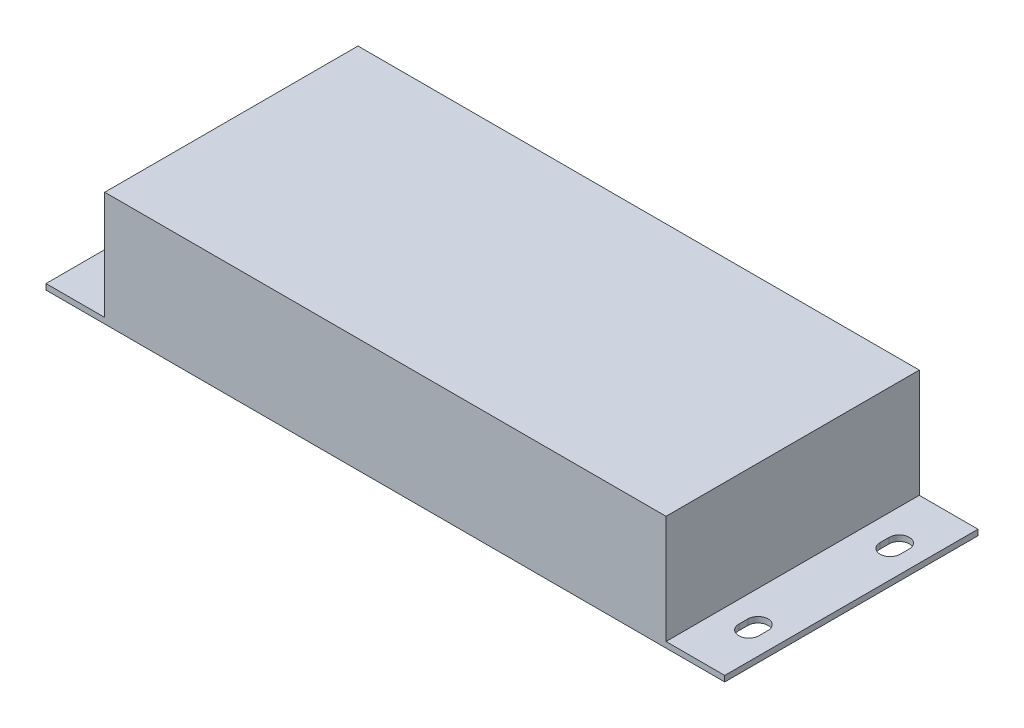
SolidWorks part; units mm, degrees
ref_plane "Front Plane" through (0, 0, 0) normal (0, 0, 1) x (1, 0, 0)
ref_plane "Top Plane" through (0, 0, 0) normal (0, 1, 0) x (1, 0, 0)
ref_plane "Right Plane" through (0, 0, 0) normal (1, 0, 0) x (0, 0, -1)
sketch "Sketch1" plane through (0, 0, 0) normal (0, 1, 0) x (1, 0, 0)
  line L1 (0, 0) -> (99.9236, 0)
  line L2 (0, 0) -> (0, 45.085)
  line L3 (0, 45.085) -> (99.9236, 45.085)
  line L4 (99.9236, 0) -> (99.9236, 45.085)
  dimension "D1" = 99.9236
  dimension "D2" = 45.085
extrude "Boss-Extrude1" add sketch "Sketch1" along normal blind 19.304
sketch "Sketch2" plane through (0, 0, 0) normal (0, -1, 0) x (1, 0, 0)
  line L0 (0, 0) -> (99.9236, -45.085) construction
  line L1 (0, 0) -> (99.9236, 0) construction
  line L2 (-10.4521, -45.085) -> (110.3757, -45.085)
  line L3 (-10.4521, -45.085) -> (-10.4521, 0)
  line L4 (-10.4521, 0) -> (110.3757, 0)
  line L5 (110.3757, -45.085) -> (110.3757, 0)
  line L6 (-10.4521, -45.085) -> (110.3757, 0) construction
  line L7 (-10.4521, 0) -> (110.3757, -45.085) construction
  line L8 (49.9618, 0) -> (49.9618, -45.085) construction
  line L9 (-5.588, -9.1567) -> (-5.588, -10.7823) construction
  line L10 (-3.7973, -9.1567) -> (-3.7973, -10.7823)
  line L11 (-7.3787, -9.1567) -> (-7.3787, -10.7823)
  line L12 (-10.4521, -22.5425) -> (110.3757, -22.5425) construction
  line L13 (-5.588, -35.9283) -> (-5.588, -34.3027) construction
  line L14 (-3.7973, -35.9283) -> (-3.7973, -34.3027)
  line L15 (-7.3787, -35.9283) -> (-7.3787, -34.3027)
  line L16 (105.5116, -9.1567) -> (105.5116, -10.7823) construction
  line L17 (103.7209, -9.1567) -> (103.7209, -10.7823)
  line L18 (107.3023, -9.1567) -> (107.3023, -10.7823)
  line L19 (105.5116, -35.9283) -> (105.5116, -34.3027) construction
  line L20 (103.7209, -35.9283) -> (103.7209, -34.3027)
  line L21 (107.3023, -35.9283) -> (107.3023, -34.3027)
  arc A0 (-3.7973, -9.1567) -> (-7.3787, -9.1567) centre (-5.588, -9.1567) ccw
  arc A1 (-7.3787, -10.7823) -> (-3.7973, -10.7823) centre (-5.588, -10.7823) ccw
  arc A2 (-3.7973, -35.9283) -> (-7.3787, -35.9283) centre (-5.588, -35.9283) cw
  arc A3 (-7.3787, -34.3027) -> (-3.7973, -34.3027) centre (-5.588, -34.3027) cw
  arc A4 (103.7209, -9.1567) -> (107.3023, -9.1567) centre (105.5116, -9.1567) cw
  arc A5 (107.3023, -10.7823) -> (103.7209, -10.7823) centre (105.5116, -10.7823) cw
  arc A6 (103.7209, -35.9283) -> (107.3023, -35.9283) centre (105.5116, -35.9283) ccw
  arc A7 (107.3023, -34.3027) -> (103.7209, -34.3027) centre (105.5116, -34.3027) ccw
  point P4 (49.9618, -22.5425)
  point P15 (-5.588, -9.9695)
  point P24 (-5.588, -35.1155)
  point P31 (105.5116, -9.9695)
  point P38 (105.5116, -35.1155)
  dimension "D1" = 120.8278
  dimension "D2" = 3.5814
  dimension "D3" = 3.0734
  dimension "D4" = 9.1567
  dimension "D5" = 1.6256
extrude "Boss-Extrude2" add sketch "Sketch2" along normal blind 1.016
ref_plane "Plane1" through (49.9618, 0, 0) normal (1, 0, 0) x (0, 0, -1)
sketch "Sketch3" plane through (0, 0, -45.085) normal (0, 0, -1) x (-1, 0, 0)
  line L0 (0, 19.304) -> (-99.9236, 0) construction
  line L2 (-6.6717, 6.7618) -> (-93.2519, 6.7618)
  line L3 (-6.6717, 6.7618) -> (-6.6717, 12.5422)
  line L4 (-6.6717, 12.5422) -> (-93.2519, 12.5422)
  line L5 (-93.2519, 6.7618) -> (-93.2519, 12.5422)
  line L6 (-6.6717, 6.7618) -> (-93.2519, 12.5422) construction
  line L7 (-6.6717, 12.5422) -> (-93.2519, 6.7618) construction
  point P4 (-49.9618, 9.652)
extrude "Cut-Extrude1" cut sketch "Sketch3" against normal blind 5
equation "\"D4@Sketch2\"=0.29in+\"D2@Sketch2\"/2"
equation "\"D5@Sketch2\"=0.205in-\"D2@Sketch2\""
